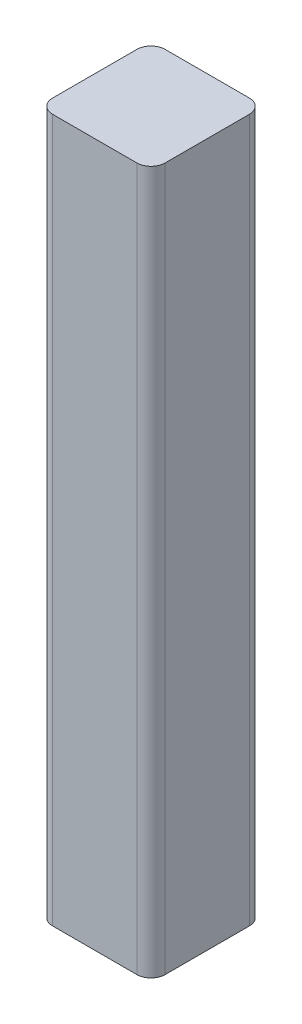
SolidWorks part; units mm, degrees
ref_plane "Front Plane" through (0, 0, 0) normal (0, 0, 1) x (1, 0, 0)
ref_plane "Top Plane" through (0, 0, 0) normal (0, 1, 0) x (1, 0, 0)
ref_plane "Right Plane" through (0, 0, 0) normal (1, 0, 0) x (0, 0, -1)
sketch "Sketch2" plane through (0, 0.2899, 7.7548) normal (0, 0, 1) x (1, 0, 0)
  line L1 (-8, 50) -> (8, 50)
  line L2 (-8, 50) -> (-8, -50)
  line L3 (-8, -50) -> (8, -50)
  line L4 (8, 50) -> (8, -50)
  dimension "D1" = 16
  dimension "D2" = 100
extrude "Boss-Extrude1" add sketch "Sketch2" against normal blind 16
fillet "Fillet1" radius 2 4 edges at (-8, 0.2899, -8.2452) (-8, 0.2899, 7.7548) (8, 0.2899, -8.2452) (8, 0.2899, 7.7548)
